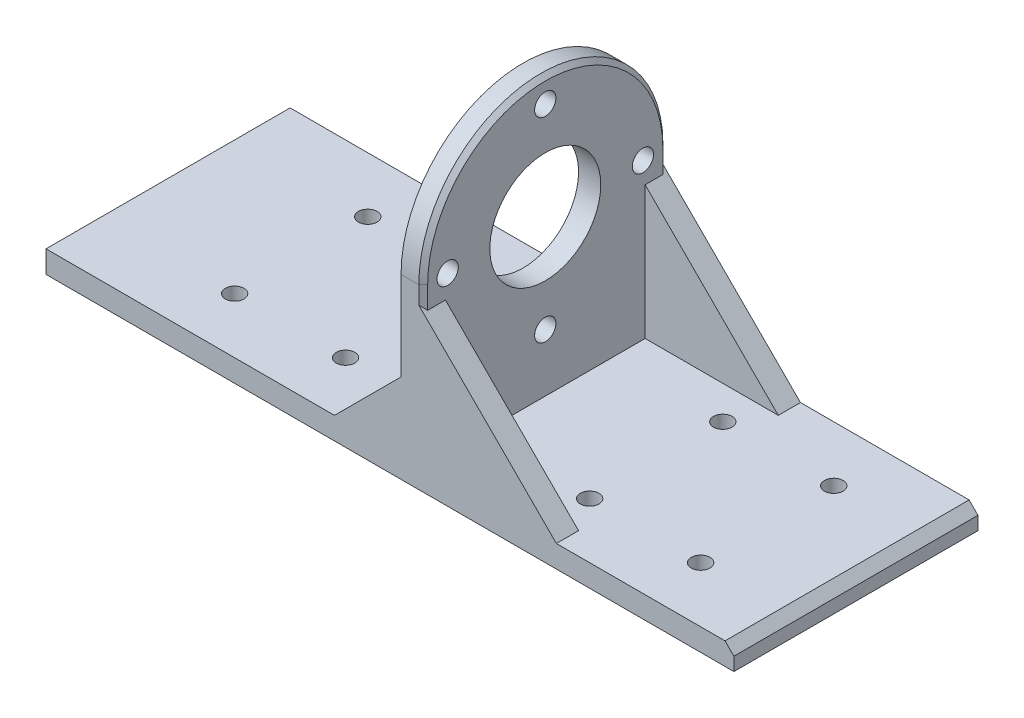
SolidWorks part; units mm, degrees
ref_plane "Front" through (0, 0, 0) normal (0, 0, 1) x (1, 0, 0)
ref_plane "Top" through (0, 0, 0) normal (0, 1, 0) x (1, 0, 0)
ref_plane "Right" through (0, 0, 0) normal (1, 0, 0) x (0, 0, -1)
sketch "草图1" plane through (0, 0, 0) normal (1, 0, 0) x (0, 0, -1)
  line L0 (-27.5, 0) -> (-27.5, -40)
  line L1 (-27.5, -40) -> (27.5, -40)
  line L2 (27.5, -40) -> (27.5, 0)
  arc A0 (27.5, 0) -> (-27.5, 0) centre (0, 0) ccw
  circle A1 centre (0, 0) radius 22 construction
  circle A2 centre (0, 0) radius 12.5
  circle A3 centre (0, 22) radius 2.4
  circle A4 centre (22, 0) radius 2.4
  circle A5 centre (0, -22) radius 2.4
  circle A6 centre (-22, 0) radius 2.4
extrude "凸台-拉伸1" add sketch "草图1" along normal blind 5
sketch "草图2" plane through (0, 0, 0) normal (-1, 0, 0) x (0, 0, 1)
  line L0 (27.5, 0) -> (27.5, -40) construction
  line L1 (-27.5, -40) -> (27.5, -40)
  line L2 (-27.5, -40) -> (-27.5, -35)
  line L3 (-27.5, -35) -> (27.5, -35)
  line L4 (27.5, -40) -> (27.5, -35)
  line L5 (0, -35) -> (0, -40) construction
  line L6 (-27.5, -37.5) -> (27.5, -37.5) construction
  point P112 (0, -37.5)
extrude "凸台-拉伸2" add sketch "草图2" along normal blind 80 contours L3 L4 L1 L2
sketch3d "3D草图1" plane through (0, 0, 0) normal (0, 0, 1) x (1, 0, 0)
  dimension "D1" = 25
sketch "草图3" plane through (0, 0, 25) normal (0, 0, 1) x (1, 0, 0)
  line L0 (0, -35) -> (0, -20) construction
  line L1 (0, 0) -> (0, -35) construction
  line L2 (0, -35) -> (-15, -35) construction
  line L3 (-80, -35) -> (0, -35) construction
  line L4 (-15, -35) -> (0, -20)
  dimension "D1" = 15
  dimension "D2" = 15
rib "筋1" sketch "草图3" sketch "草图3" thickness 5 extrusion direction parallel to sketch draft on no parameters "D1"=5
mirror "镜向1" about plane through (0, 0, 0) normal (0, 0, 1) of "筋1"
chamfer "倒角2" distance 5 angle 45 1 edges at (0, -35, 0)
sketch "草图4" plane through (5, 0, 0) normal (1, 0, 0) x (0, 0, -1)
  line L0 (27.5, -40) -> (27.5, 0) construction
  line L1 (-27.5, -40) -> (27.5, -40)
  line L2 (-27.5, -40) -> (-27.5, -35)
  line L3 (-27.5, -35) -> (27.5, -35)
  line L4 (27.5, -40) -> (27.5, -35)
  line L5 (0, -35) -> (0, -40) construction
  line L6 (-27.5, -37.5) -> (27.5, -37.5) construction
  point P160 (0, -37.5)
extrude "凸台-拉伸3" add sketch "草图4" along normal blind 70
sketch "草图5" plane through (0, 0, 25) normal (0, 0, 1) x (1, 0, 0)
  line L0 (5, -35) -> (5, -5) construction
  line L1 (5, 0) -> (5, -35) construction
  line L2 (5, -35) -> (35, -35) construction
  line L3 (75, -35) -> (5, -35) construction
  line L4 (35, -35) -> (5, -5)
rib "筋6" sketch "草图5" sketch "草图5" thickness 5 extrusion direction parallel to sketch draft on no parameters "D1"=5
mirror "镜向2" about plane through (0, 0, 0) normal (0, 0, 1) of "筋6"
sketch "草图6" plane through (0, -35, 0) normal (0, 1, 0) x (1, 0, 0)
  line L0 (5, 0) -> (5, 15) construction
  line L1 (5, 22.5) -> (5, -22.5) construction
  line L2 (5, 15) -> (75, 15) construction
  line L3 (75, 27.5) -> (75, -27.5) construction
  line L4 (5, 15) -> (-80, 15) construction
  line L5 (-80, 27.5) -> (-80, -27.5) construction
  line L6 (5, 15) -> (30, 15) construction
  line L7 (30, 15) -> (55, 15) construction
  line L8 (5, 15) -> (-25, 15) construction
  line L9 (-25, 15) -> (-50, 15) construction
  line L10 (0, 0) -> (20, 0) construction
  line L11 (-80, 27.5) -> (-15, 27.5) construction
  circle A0 centre (30, 15) radius 2.1
  circle A1 centre (55, 15) radius 2.1
  circle A2 centre (-50, 15) radius 2.1
  circle A3 centre (-25, 15) radius 2.1
  circle A4 centre (55, -15) radius 2.1
  circle A5 centre (30, -15) radius 2.1
  circle A6 centre (-25, -15) radius 2.1
  circle A7 centre (-50, -15) radius 2.1
  dimension "D1" = 30
  dimension "D2" = 25
  dimension "D3" = 20
  dimension "D4" = 25
  dimension "D5" = 12.5
extrude "切除-拉伸1" cut sketch "草图6" against normal up to next
chamfer "倒角3" distance 1 angle 45 3 edges at (5, -2.5, -27.5) (5, -2.5, 27.5) (5, 27.5, 0)
chamfer "倒角4" distance 2 angle 45 1 edges at (75, -35, 0)
